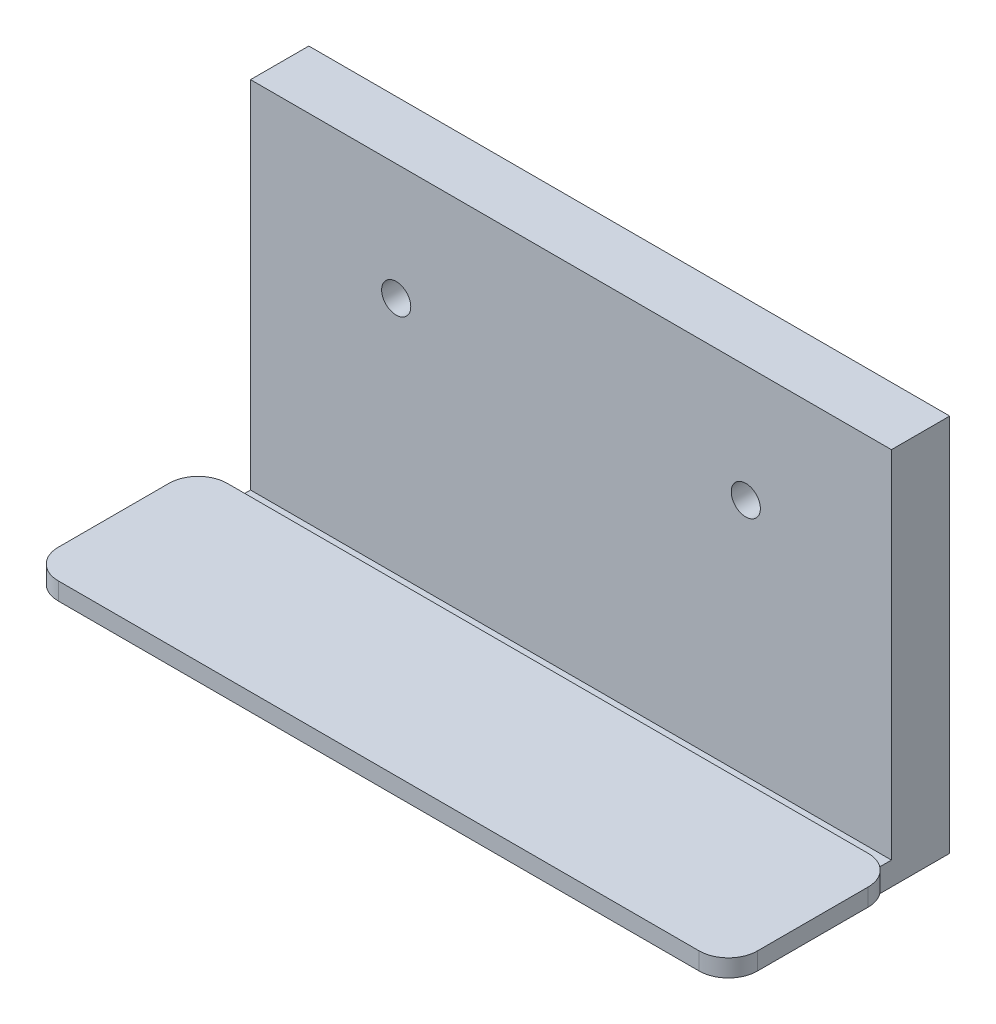
SolidWorks part; units mm, degrees
ref_plane "Front Plane" through (0, 0, 0) normal (0, 0, 1) x (1, 0, 0)
ref_plane "Top Plane" through (0, 0, 0) normal (0, 1, 0) x (1, 0, 0)
ref_plane "Right Plane" through (0, 0, 0) normal (1, 0, 0) x (0, 0, -1)
sketch "Esquisse1" plane through (0, 0, 0) normal (0, 0, 1) x (1, 0, 0)
  line L1 (-55, -32.5) -> (55, -32.5)
  line L2 (-55, -32.5) -> (-55, 32.5)
  line L3 (-55, 32.5) -> (55, 32.5)
  line L4 (55, -32.5) -> (55, 32.5)
  line L5 (-55, -32.5) -> (55, 32.5) construction
  line L6 (-55, 32.5) -> (55, -32.5) construction
  point P0 (0, 0)
  dimension "D1" = 65
  dimension "D2" = 110
extrude "Boss.-Extru.1" add sketch "Esquisse1" along normal blind 10
ref_plane "Plan1" through (0, 0, 10) normal (0, 0, 1) x (1, 0, 0)
sketch "Esquisse2" plane through (0, 0, 10) normal (0, 0, 1) x (1, 0, 0)
  line L0 (55, -32.5) -> (55, 32.5) construction
  line L1 (-55, -32.5) -> (55, -32.5)
  line L2 (-55, -32.5) -> (-55, -28.5)
  line L3 (-55, -28.5) -> (55, -28.5)
  line L4 (55, -32.5) -> (55, -28.5)
  dimension "D1" = 4
extrude "Boss.-Extru.2" add sketch "Esquisse2" along normal blind 20
ref_plane "Plan2" through (0, -28.5, 0) normal (0, 1, 0) x (1, 0, 0)
sketch "Esquisse3" plane through (0, -28.5, 0) normal (0, 1, 0) x (1, 0, 0)
  line L0 (55, -10) -> (-55, -10) construction
  line L1 (60, -14) -> (-60, -14)
  line L2 (60, -14) -> (60, -43)
  line L3 (60, -43) -> (-60, -43)
  line L4 (-60, -14) -> (-60, -43)
  line L5 (-55, -30) -> (-55, -10) construction
  line L6 (55, -30) -> (55, -10) construction
  dimension "D1" = 4
  dimension "D2" = 29
  dimension "D3" = 5
  dimension "D4" = 5
extrude "Boss.-Extru.3" add sketch "Esquisse3" along normal blind 3
fillet "Congé1" radius 5 4 edges at (60, -27, 14) (60, -27, 43) (-60, -27, 43) (-60, -27, 14)
sketch "Esquisse4" plane through (0, 0, 10) normal (0, 0, 1) x (1, 0, 0)
  line L0 (55, 32.5) -> (-55, 32.5) construction
  line L1 (-55, 32.5) -> (-55, -28.5) construction
  line L2 (55, -28.5) -> (55, 32.5) construction
  circle A0 centre (-30, 12.5) radius 2.5
  circle A1 centre (30, 12.5) radius 2.5
  dimension "D1" = 5
  dimension "D2" = 5
  dimension "D3" = 20
  dimension "D4" = 20
  dimension "D5" = 25
  dimension "D6" = 25
extrude "Enlèv. mat.-Extru.1" cut sketch "Esquisse4" against normal through all
